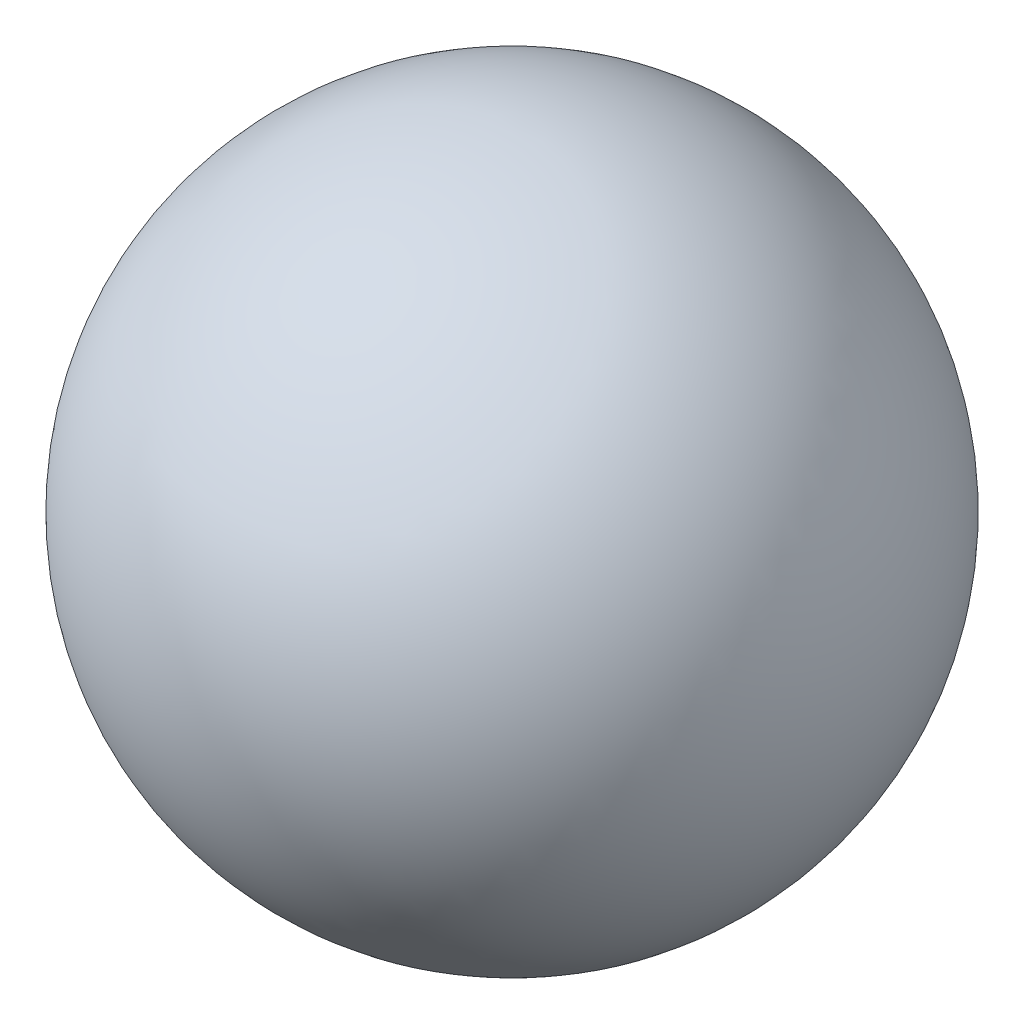
SolidWorks part; units mm, degrees
material "PVC 0.007 塑化"
ref_plane "前基準面" through (0, 0, 0) normal (0, 0, 1) x (1, 0, 0)
ref_plane "上基準面" through (0, 0, 0) normal (0, 1, 0) x (1, 0, 0)
ref_plane "右基準面" through (0, 0, 0) normal (1, 0, 0) x (0, 0, -1)
sketch "草圖1" plane through (0, 0, 0) normal (0, 0, 1) x (1, 0, 0)
  line L0 (0, 35) -> (0, -35)
  arc A0 (0, 35) -> (0, -35) centre (0, 0) cw
  point P4 (0, 0)
  dimension "D1" = 35
revolve "旋轉1" add sketch "草圖1" angle 360 about L0
